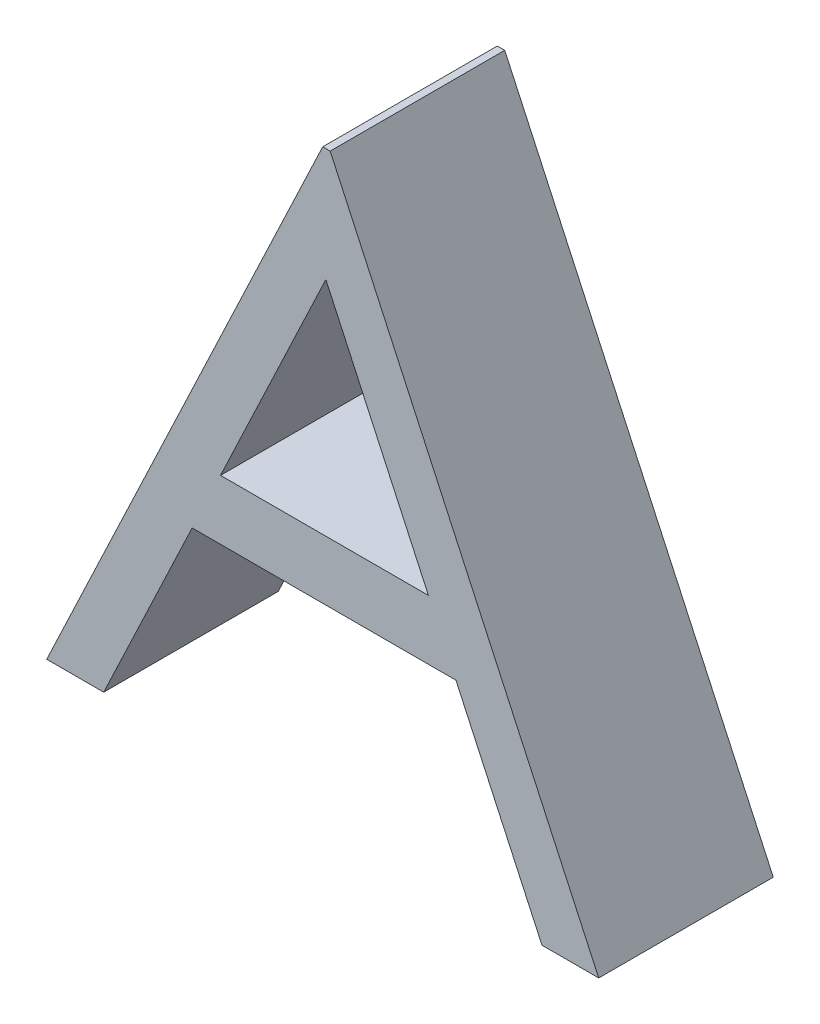
SolidWorks part; units mm, degrees
ref_plane "Plan de face" through (0, 0, 0) normal (0, 0, 1) x (1, 0, 0)
ref_plane "Plan de dessus" through (0, 0, 0) normal (0, 1, 0) x (1, 0, 0)
ref_plane "Plan de droite" through (0, 0, 0) normal (1, 0, 0) x (0, 0, -1)
sketch "Esquisse1" plane through (0, 0, 0) normal (0, 0, 1) x (1, 0, 0)
  text T0 "A" font "Century Gothic" height 5
extrude "Boss.-Extru.1" add sketch "Esquisse1" along normal blind 1.5
